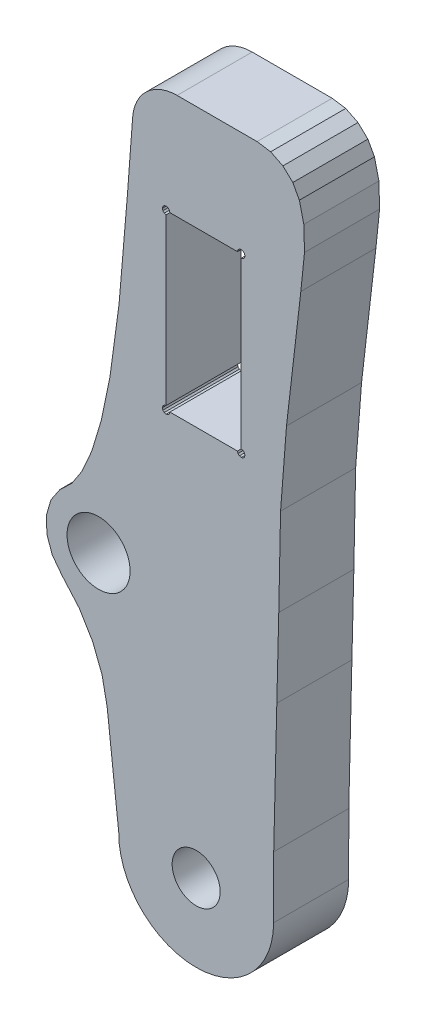
SolidWorks part; units mm, degrees
ref_plane "Plan de face" through (0, 0, 0) normal (0, 0, 1) x (1, 0, 0)
ref_plane "Plan de dessus" through (0, 0, 0) normal (0, 1, 0) x (1, 0, 0)
ref_plane "Plan de droite" through (0, 0, 0) normal (1, 0, 0) x (0, 0, -1)
ref_plane "Plan1" through (0, 0, 5) normal (0, 0, 1) x (1, 0, 0)
sketch "Esquisse1" plane through (0, 0, 5) normal (0, 0, 1) x (1, 0, 0)
  line L0 (14.25, 42.65) -> (14.2835, 42.775)
  line L1 (14.2835, 42.775) -> (14.375, 42.8665)
  line L2 (14.375, 42.8665) -> (14.5, 42.9)
  line L3 (14.5, 42.9) -> (14.625, 42.8665)
  line L4 (14.625, 42.8665) -> (14.7165, 42.775)
  line L5 (14.7165, 42.775) -> (14.75, 42.65)
  line L6 (14.75, 42.65) -> (19.25, 42.65)
  line L7 (19.25, 42.65) -> (19.2835, 42.775)
  line L8 (19.2835, 42.775) -> (19.375, 42.8665)
  line L9 (19.375, 42.8665) -> (19.5, 42.9)
  line L10 (19.5, 42.9) -> (19.625, 42.8665)
  line L11 (19.625, 42.8665) -> (19.7165, 42.775)
  line L12 (19.7165, 42.775) -> (19.75, 42.65)
  line L13 (19.75, 42.65) -> (19.7165, 42.525)
  line L14 (19.7165, 42.525) -> (19.625, 42.4335)
  line L15 (19.625, 42.4335) -> (19.5, 42.4)
  line L16 (19.5, 42.4) -> (19.5, 31.4)
  line L17 (19.5, 31.4) -> (19.625, 31.3665)
  line L18 (19.625, 31.3665) -> (19.7165, 31.275)
  line L19 (19.7165, 31.275) -> (19.75, 31.15)
  line L20 (19.75, 31.15) -> (19.7165, 31.025)
  line L21 (19.7165, 31.025) -> (19.625, 30.9335)
  line L22 (19.625, 30.9335) -> (19.5, 30.9)
  line L23 (19.5, 30.9) -> (19.375, 30.9335)
  line L24 (19.375, 30.9335) -> (19.2835, 31.025)
  line L25 (19.2835, 31.025) -> (19.25, 31.15)
  line L26 (19.25, 31.15) -> (14.75, 31.15)
  line L27 (14.75, 31.15) -> (14.7165, 31.025)
  line L28 (14.7165, 31.025) -> (14.625, 30.9335)
  line L29 (14.625, 30.9335) -> (14.5, 30.9)
  line L30 (14.5, 30.9) -> (14.375, 30.9335)
  line L31 (14.375, 30.9335) -> (14.2835, 31.025)
  line L32 (14.2835, 31.025) -> (14.25, 31.15)
  line L33 (14.25, 31.15) -> (14.2835, 31.275)
  line L34 (14.2835, 31.275) -> (14.375, 31.3665)
  line L35 (14.375, 31.3665) -> (14.5, 31.4)
  line L36 (14.5, 31.4) -> (14.5, 42.4)
  line L37 (14.5, 42.4) -> (14.375, 42.4335)
  line L38 (14.375, 42.4335) -> (14.2835, 42.525)
  line L39 (14.2835, 42.525) -> (14.25, 42.65)
  line L40 (21.6636, 9.2467) -> (21.6563, 5.1494)
  line L50 (21.6636, 9.2467) -> (21.8702, 17.918)
  line L51 (21.8702, 17.918) -> (22, 23.2122)
  line L52 (22, 23.2122) -> (22.1198, 29.1198)
  line L53 (22.1198, 29.1198) -> (22.5141, 34.2292)
  line L54 (22.5141, 34.2292) -> (23.4694, 42.464)
  line L55 (23.4694, 42.464) -> (23.7138, 44.8357)
  line L56 (23.7138, 44.8357) -> (23.6681, 46.4336)
  line L57 (23.6681, 46.4336) -> (23.3738, 47.6799)
  line L58 (23.3738, 47.6799) -> (22.9343, 48.4787)
  line L59 (22.9343, 48.4787) -> (22.2752, 49.1086)
  line L60 (22.2752, 49.1086) -> (21.4572, 49.5115)
  line L61 (21.4572, 49.5115) -> (20.5561, 49.65)
  line L62 (20.5561, 49.65) -> (15.2296, 49.65)
  line L67 (12.2681, 46.9011) -> (11.9276, 42.3361)
  line L68 (11.9276, 42.3361) -> (11.3695, 35.7322)
  line L69 (11.3695, 35.7322) -> (10.766, 31.2245)
  line L70 (10.766, 31.2245) -> (10.1868, 28.4092)
  line L71 (10.1868, 28.4092) -> (9.5562, 26.3119)
  line L72 (9.5562, 26.3119) -> (8.891, 24.7985)
  line L73 (8.891, 24.7985) -> (8.2042, 23.7525)
  line L74 (8.2042, 23.7525) -> (7.43, 23.026)
  line L75 (7.43, 23.026) -> (6.8275, 22.1283)
  line L76 (6.8275, 22.1283) -> (6.5277, 21.0897)
  line L77 (6.5277, 21.0897) -> (6.5592, 20.009)
  line L78 (6.5592, 20.009) -> (6.9189, 18.9896)
  line L79 (6.9189, 18.9896) -> (7.5726, 18.1285)
  line L80 (7.5726, 18.1285) -> (8.7098, 16.8263)
  line L81 (8.7098, 16.8263) -> (9.6057, 15.3478)
  line L82 (9.6057, 15.3478) -> (10.2336, 13.737)
  line L83 (10.2336, 13.737) -> (10.5746, 12.0422)
  line L84 (10.5746, 12.0422) -> (11.344, 5.2037)
  circle A0 centre (10, 20.65) radius 2.1
  circle A1 centre (16.5, 5.1501) radius 1.6
  arc A2 (12.2681, 46.9011) -> (15.2296, 49.65) centre (15.2296, 46.6802) cw
  arc A3 (11.344, 5.2037) -> (21.6563, 5.1494) centre (16.5, 5.1501) ccw
  dimension "D1" = 4.2
  dimension "D2" = 3.2
extrude "Boss.-Extru.1" add sketch "Esquisse1" against normal blind 5
